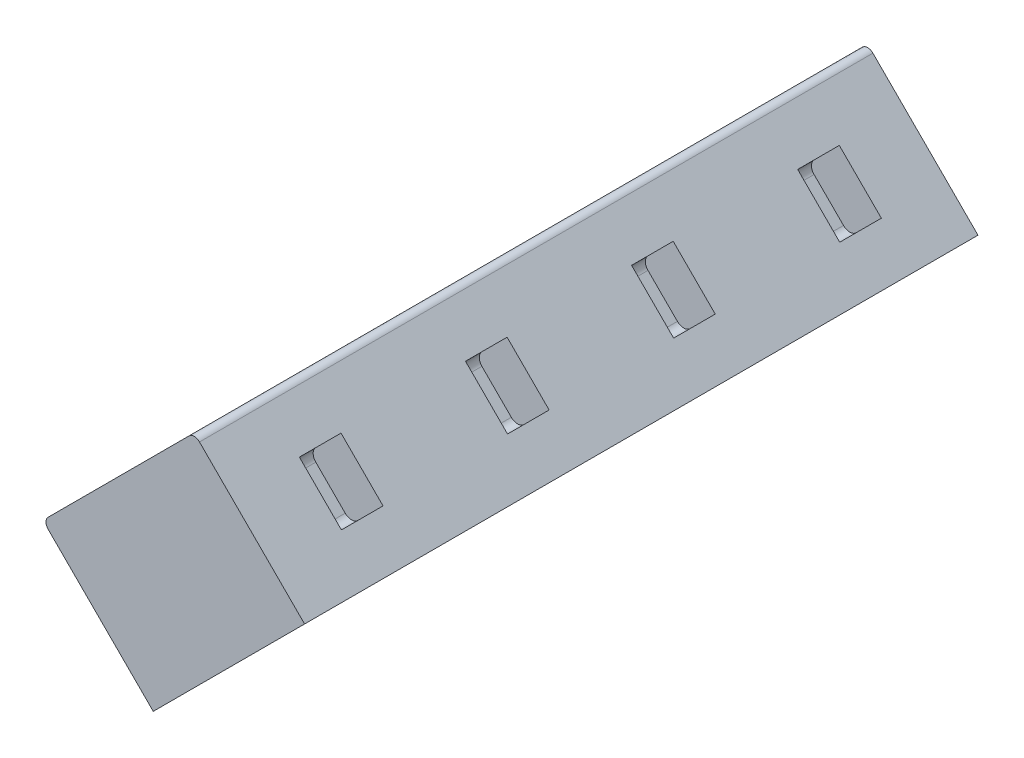
SolidWorks part; units mm, degrees
ref_plane "Front Plane" through (0, 0, 0) normal (0, 0, 1) x (1, 0, 0)
ref_plane "Top Plane" through (0, 0, 0) normal (0, 1, 0) x (1, 0, 0)
ref_plane "Right Plane" through (0, 0, 0) normal (1, 0, 0) x (0, 0, -1)
other "Configuration Table"
sketch "Sketch1" plane through (0, 0, 0) normal (0, 0, 1) x (1, 0, 0)
  line L0 (-115.223, 217.0464) -> (-217.0464, 115.223)
  line L1 (-217.0464, 115.223) -> (-287.7571, 185.9337)
  line L2 (-287.7571, 193.0048) -> (-193.0048, 287.7571)
  line L3 (-185.9337, 287.7571) -> (-115.223, 217.0464)
  arc A0 (-287.7571, 185.9337) -> (-287.7571, 193.0048) centre (-284.2216, 189.4693) cw
  arc A1 (-193.0048, 287.7571) -> (-185.9337, 287.7571) centre (-189.4693, 284.2216) cw
extrude "Head Casting" add sketch "Sketch1" along normal blind 453.1 from offset 405
sketch "Sketch2" plane through (0, 0, 0) normal (0, 0, 1) x (1, 0, 0)
  line L0 (-135.7291, 238.9667) -> (-153.4068, 221.2891)
  line L1 (-161.8921, 221.2891) -> (-181.6911, 241.0881)
  line L2 (-181.6911, 249.5733) -> (-164.0134, 267.251)
  line L3 (-164.0134, 267.251) -> (-135.7291, 238.9667)
  arc A0 (-153.4068, 221.2891) -> (-161.8921, 221.2891) centre (-157.6495, 225.5317) cw
  arc A1 (-181.6911, 241.0881) -> (-181.6911, 249.5733) centre (-177.4484, 245.3307) cw
extrude "Intake Port 2" cut sketch "Sketch2" along normal blind 28 from offset 25.9
sketch "Sketch3" plane through (0, 0, 0) normal (0, 0, 1) x (1, 0, 0)
  line L0 (-240.381, 137.1434) -> (-224.1175, 153.4068)
  line L1 (-224.1175, 164.7205) -> (-238.2596, 178.8627)
  line L2 (-249.5733, 178.8627) -> (-265.8368, 162.5992)
  line L3 (-265.8368, 162.5992) -> (-240.381, 137.1434)
  arc A0 (-224.1175, 153.4068) -> (-224.1175, 164.7205) centre (-229.7743, 159.0637) ccw
  arc A1 (-238.2596, 178.8627) -> (-249.5733, 178.8627) centre (-243.9165, 173.2058) ccw
extrude "Exhaust Port 2" cut sketch "Sketch3" along normal blind 32 from offset 27.9
sketch "Sketch4" plane through (0, 0, 0) normal (0, 0, 1) x (1, 0, 0)
  line L0 (-135.7291, 238.9667) -> (-153.4068, 221.2891)
  line L1 (-161.8921, 221.2891) -> (-181.6911, 241.0881)
  line L2 (-181.6911, 249.5733) -> (-164.0134, 267.251)
  line L3 (-164.0134, 267.251) -> (-135.7291, 238.9667)
  arc A0 (-153.4068, 221.2891) -> (-161.8921, 221.2891) centre (-157.6495, 225.5317) cw
  arc A1 (-181.6911, 241.0881) -> (-181.6911, 249.5733) centre (-177.4484, 245.3307) cw
extrude "Intake Port 4" cut sketch "Sketch4" along normal blind 28 from offset 137.66
sketch "Sketch5" plane through (0, 0, 0) normal (0, 0, 1) x (1, 0, 0)
  line L0 (-240.381, 137.1434) -> (-224.1175, 153.4068)
  line L1 (-224.1175, 164.7205) -> (-238.2596, 178.8627)
  line L2 (-249.5733, 178.8627) -> (-265.8368, 162.5992)
  line L3 (-265.8368, 162.5992) -> (-240.381, 137.1434)
  arc A0 (-224.1175, 153.4068) -> (-224.1175, 164.7205) centre (-229.7743, 159.0637) ccw
  arc A1 (-238.2596, 178.8627) -> (-249.5733, 178.8627) centre (-243.9165, 173.2058) ccw
extrude "Exhaust Port 4" cut sketch "Sketch5" along normal blind 32 from offset 139.66
sketch "Sketch6" plane through (0, 0, 0) normal (0, 0, 1) x (1, 0, 0)
  line L0 (-135.7291, 238.9667) -> (-153.4068, 221.2891)
  line L1 (-161.8921, 221.2891) -> (-181.6911, 241.0881)
  line L2 (-181.6911, 249.5733) -> (-164.0134, 267.251)
  line L3 (-164.0134, 267.251) -> (-135.7291, 238.9667)
  arc A0 (-153.4068, 221.2891) -> (-161.8921, 221.2891) centre (-157.6495, 225.5317) cw
  arc A1 (-181.6911, 241.0881) -> (-181.6911, 249.5733) centre (-177.4484, 245.3307) cw
extrude "Intake Port 6" cut sketch "Sketch6" along normal blind 28 from offset 249.42
sketch "Sketch7" plane through (0, 0, 0) normal (0, 0, 1) x (1, 0, 0)
  line L0 (-240.381, 137.1434) -> (-224.1175, 153.4068)
  line L1 (-224.1175, 164.7205) -> (-238.2596, 178.8627)
  line L2 (-249.5733, 178.8627) -> (-265.8368, 162.5992)
  line L3 (-265.8368, 162.5992) -> (-240.381, 137.1434)
  arc A0 (-224.1175, 153.4068) -> (-224.1175, 164.7205) centre (-229.7743, 159.0637) ccw
  arc A1 (-238.2596, 178.8627) -> (-249.5733, 178.8627) centre (-243.9165, 173.2058) ccw
extrude "Exhaust Port 6" cut sketch "Sketch7" along normal blind 32 from offset 251.42
sketch "Sketch8" plane through (0, 0, 0) normal (0, 0, 1) x (1, 0, 0)
  line L0 (-135.7291, 238.9667) -> (-153.4068, 221.2891)
  line L1 (-161.8921, 221.2891) -> (-181.6911, 241.0881)
  line L2 (-181.6911, 249.5733) -> (-164.0134, 267.251)
  line L3 (-164.0134, 267.251) -> (-135.7291, 238.9667)
  arc A0 (-153.4068, 221.2891) -> (-161.8921, 221.2891) centre (-157.6495, 225.5317) cw
  arc A1 (-181.6911, 241.0881) -> (-181.6911, 249.5733) centre (-177.4484, 245.3307) cw
extrude "Intake Port 8" cut sketch "Sketch8" along normal blind 28 from offset 361.18
sketch "Sketch9" plane through (0, 0, 0) normal (0, 0, 1) x (1, 0, 0)
  line L0 (-240.381, 137.1434) -> (-224.1175, 153.4068)
  line L1 (-224.1175, 164.7205) -> (-238.2596, 178.8627)
  line L2 (-249.5733, 178.8627) -> (-265.8368, 162.5992)
  line L3 (-265.8368, 162.5992) -> (-240.381, 137.1434)
  arc A0 (-224.1175, 153.4068) -> (-224.1175, 164.7205) centre (-229.7743, 159.0637) ccw
  arc A1 (-238.2596, 178.8627) -> (-249.5733, 178.8627) centre (-243.9165, 173.2058) ccw
extrude "Exhaust Port 8" cut sketch "Sketch9" along normal blind 32 from offset 363.18
